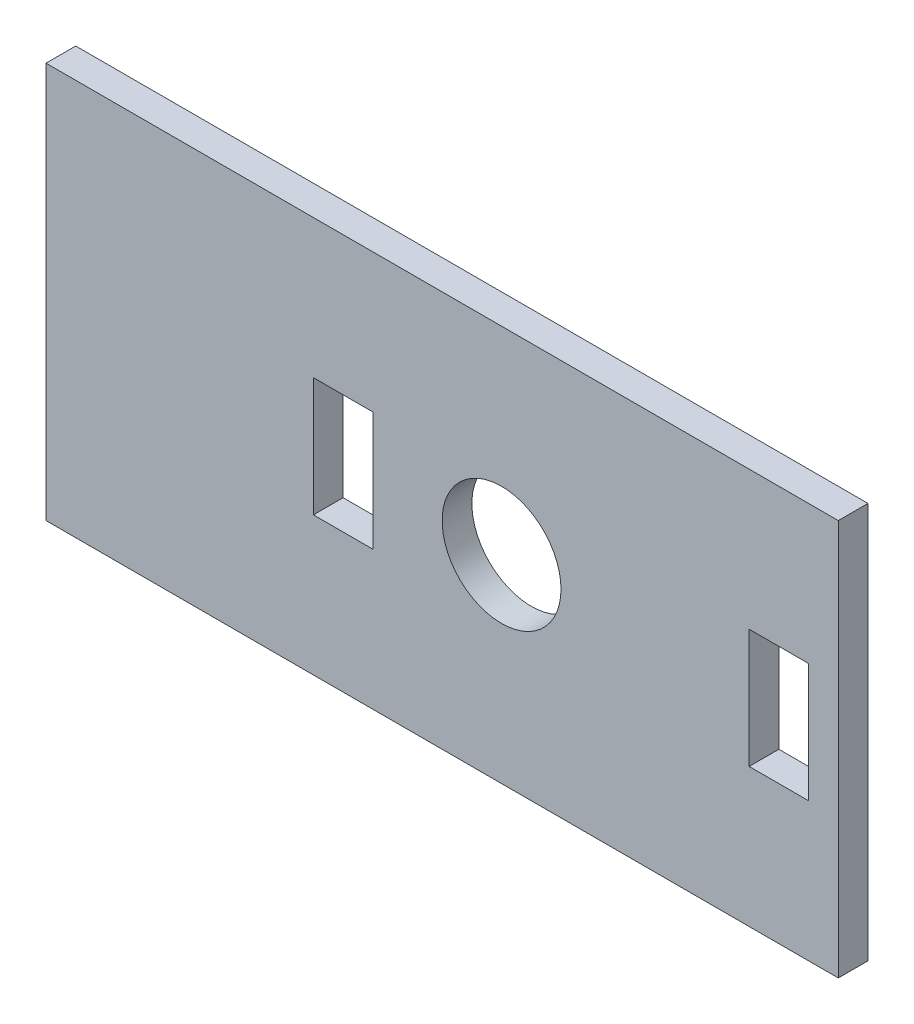
SolidWorks part; units mm, degrees
ref_plane "前视基准面" through (0, 0, 0) normal (0, 0, 1) x (1, 0, 0)
ref_plane "上视基准面" through (0, 0, 0) normal (0, 1, 0) x (1, 0, 0)
ref_plane "右视基准面" through (0, 0, 0) normal (1, 0, 0) x (0, 0, -1)
sketch "草图1" plane through (0, 0, 0) normal (0, 0, 1) x (1, 0, 0)
  line L0 (-62.6146, 0) -> (72.2372, 0) construction
  line L1 (-20, 10) -> (20, 10)
  line L2 (-20, 10) -> (-20, -10)
  line L3 (-20, -10) -> (20, -10)
  line L4 (20, 10) -> (20, -10)
  line L5 (-20, 10) -> (20, -10) construction
  line L6 (-20, -10) -> (20, 10) construction
  line L8 (-6.5, 3) -> (-3.5, 3)
  line L9 (-6.5, 3) -> (-6.5, -3)
  line L10 (-6.5, -3) -> (-3.5, -3)
  line L11 (-3.5, 3) -> (-3.5, -3)
  line L12 (-6.5, 3) -> (-3.5, -3) construction
  line L13 (-6.5, -3) -> (-3.5, 3) construction
  line L14 (15.5, 3) -> (18.5, 3)
  line L15 (15.5, 3) -> (15.5, -3)
  line L16 (15.5, -3) -> (18.5, -3)
  line L17 (18.5, 3) -> (18.5, -3)
  line L18 (15.5, 3) -> (18.5, -3) construction
  line L19 (15.5, -3) -> (18.5, 3) construction
  circle A0 centre (3, 0) radius 3
  point P0 (0, 0)
  point P8 (-5, 0)
  point P15 (17, 0)
  dimension "D5" = 6
  dimension "D1" = 20
  dimension "D2" = 40
  dimension "D3" = 3
  dimension "D4" = 6
  dimension "D6" = 6
  dimension "D7" = 3
  dimension "D8" = 13.5
  dimension "D9" = 8
  dimension "D10" = 14
extrude "凸台-拉伸1" add sketch "草图1" along normal blind 1.5
